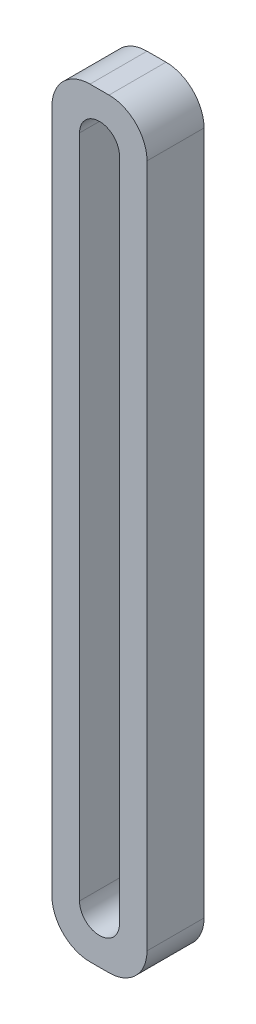
SolidWorks part; units mm, degrees
ref_plane "Front Plane" through (0, 0, 0) normal (0, 0, 1) x (1, 0, 0)
ref_plane "Top Plane" through (0, 0, 0) normal (0, 1, 0) x (1, 0, 0)
ref_plane "Right Plane" through (0, 0, 0) normal (1, 0, 0) x (0, 0, -1)
sketch "Sketch1" plane through (0, 0, 0) normal (0, 0, 1) x (1, 0, 0)
  line L0 (2.5, 37.5) -> (2.5, 2.5) construction
  line L1 (0, 0) -> (5, 0)
  line L2 (0, 0) -> (0, 40)
  line L3 (0, 40) -> (5, 40)
  line L4 (5, 0) -> (5, 40)
  line L5 (3.55, 37.5) -> (3.55, 2.5)
  line L6 (1.45, 37.5) -> (1.45, 2.5)
  arc A0 (3.55, 37.5) -> (1.45, 37.5) centre (2.5, 37.5) ccw
  arc A1 (1.45, 2.5) -> (3.55, 2.5) centre (2.5, 2.5) ccw
  point P7 (2.5, 20)
  point P12 (2.5, 40)
  point P13 (0, 0)
  point P14 (0, 20)
  dimension "D1" = 5
  dimension "D2" = 40
  dimension "D3" = 2.1
  dimension "D4" = 35
extrude "Boss-Extrude1" add sketch "Sketch1" along normal blind 3
fillet "Fillet1" radius 2 4 edges at (5, 0, 1.5) (0, 0, 1.5) (0, 40, 1.5) (5, 40, 1.5)
